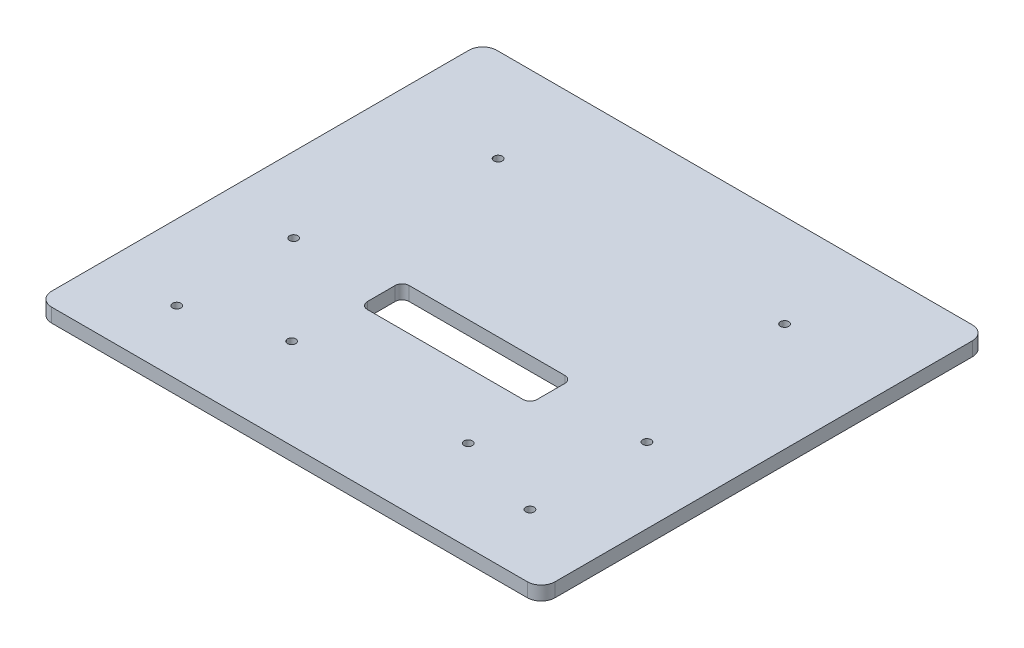
SolidWorks part; units mm, degrees
material "Acrílico (médio-alto impacto)"
ref_plane "Plano frontal" through (0, 0, 0) normal (0, 0, 1) x (1, 0, 0)
ref_plane "Plano superior" through (0, 0, 0) normal (0, 1, 0) x (1, 0, 0)
ref_plane "Plano direito" through (0, 0, 0) normal (1, 0, 0) x (0, 0, -1)
sketch "Esboço1" plane through (0, 0, 0) normal (0, 1, 0) x (1, 0, 0)
  line L1 (-61.8658, 131.6616) -> (109.1342, 131.6616)
  line L2 (-66.8658, 126.6616) -> (-66.8658, -23.3384)
  line L3 (-61.8658, -28.3384) -> (109.1342, -28.3384)
  line L4 (114.1342, 126.6616) -> (114.1342, -23.3384)
  arc A0 (109.1342, 131.6616) -> (114.1342, 126.6616) centre (109.1342, 126.6616) cw
  arc A1 (109.1342, -28.3384) -> (114.1342, -23.3384) centre (109.1342, -23.3384) ccw
  arc A2 (-61.8658, -28.3384) -> (-66.8658, -23.3384) centre (-61.8658, -23.3384) cw
  arc A3 (-61.8658, 131.6616) -> (-66.8658, 126.6616) centre (-61.8658, 126.6616) ccw
  dimension "D1" = 5
extrude "Ressalto-extrusão1" add sketch "Esboço1" along normal blind 5
sketch "Esboço2" plane through (0, 5, 0) normal (0, 1, 0) x (1, 0, 0)
  line L0 (-66.8658, 126.6616) -> (-66.8658, -23.3384) construction
  line L1 (-32.8658, 113.1616) -> (80.1342, 113.1616) construction
  line L2 (-37.8658, 108.1616) -> (-37.8658, -4.8384) construction
  line L3 (-32.8658, -9.8384) -> (80.1342, -9.8384) construction
  line L4 (85.1342, 108.1616) -> (85.1342, -4.8384) construction
  line L6 (114.1342, -23.3384) -> (114.1342, 126.6616) construction
  line L7 (109.1342, 131.6616) -> (-61.8658, 131.6616) construction
  line L9 (-61.8658, -28.3384) -> (109.1342, -28.3384) construction
  circle A0 centre (-27.8658, 98.1616) radius 1.5
  circle A1 centre (75.1342, 98.1616) radius 1.5
  circle A2 centre (-8.1158, 4.1616) radius 1.5
  circle A3 centre (55.3842, 4.1616) radius 1.5
  arc A4 (85.1342, -4.8384) -> (80.1342, -9.8384) centre (80.1342, -4.8384) cw construction
  arc A5 (-32.8658, -9.8384) -> (-37.8658, -4.8384) centre (-32.8658, -4.8384) cw construction
  arc A6 (85.1342, 108.1616) -> (80.1342, 113.1616) centre (80.1342, 108.1616) ccw construction
  arc A7 (-32.8658, 113.1616) -> (-37.8658, 108.1616) centre (-32.8658, 108.1616) ccw construction
  dimension "D5" = 15
  dimension "D7" = 15
  dimension "D8" = 10
  dimension "D9" = 29.75
  dimension "D11" = 29.75
  dimension "D12" = 5
  dimension "D13" = 14
  dimension "D1" = 29
  dimension "D2" = 29
  dimension "D3" = 18.5
  dimension "D4" = 18.5
  dimension "D6" = 10
  dimension "D10" = 14
extrude "Corte-extrusão1" cut sketch "Esboço2" against normal blind 5
sketch "Esboço3" plane through (0, 5, 0) normal (0, 1, 0) x (1, 0, 0)
  line L0 (109.1342, 131.6616) -> (-61.8658, 131.6616) construction
  line L1 (-66.8658, 126.6616) -> (-66.8658, -23.3384) construction
  line L2 (114.1342, -23.3384) -> (114.1342, 126.6616) construction
  circle A0 centre (-39.8658, 36.6616) radius 1.5
  circle A1 centre (-39.8658, -5.3884) radius 1.5
  circle A2 centre (87.1342, 36.6616) radius 1.5
  circle A3 centre (87.1342, -5.3884) radius 1.5
  dimension "D1" = 42.05
  dimension "D2" = 95
  dimension "D3" = 27
  dimension "D4" = 27
  dimension "D5" = 3
  dimension "D6" = 3
  dimension "D7" = 27
  dimension "D8" = 95
  dimension "D9" = 27
  dimension "D10" = 42.05
extrude "Corte-extrusão2" cut sketch "Esboço3" against normal blind 10
sketch "Esboço4" plane through (0, 5, 0) normal (0, 1, 0) x (1, 0, 0)
  line L0 (-66.8658, 126.6616) -> (-66.8658, -23.3384) construction
  line L1 (-4.3658, 42.6616) -> (51.6342, 42.6616)
  line L2 (-6.8658, 40.1616) -> (-6.8658, 30.1616)
  line L3 (-4.3658, 27.6616) -> (51.6342, 27.6616)
  line L4 (54.1342, 40.1616) -> (54.1342, 30.1616)
  line L5 (114.1342, -23.3384) -> (114.1342, 126.6616) construction
  line L6 (-61.8658, -28.3384) -> (109.1342, -28.3384) construction
  arc A0 (54.1342, 40.1616) -> (51.6342, 42.6616) centre (51.6342, 40.1616) ccw
  arc A1 (54.1342, 30.1616) -> (51.6342, 27.6616) centre (51.6342, 30.1616) cw
  arc A2 (-4.3658, 27.6616) -> (-6.8658, 30.1616) centre (-4.3658, 30.1616) cw
  arc A3 (-4.3658, 42.6616) -> (-6.8658, 40.1616) centre (-4.3658, 40.1616) ccw
  dimension "D4" = 2.5
  dimension "D1" = 60
  dimension "D2" = 60
  dimension "D3" = 56
extrude "Corte-extrusão3" cut sketch "Esboço4" against normal blind 10
